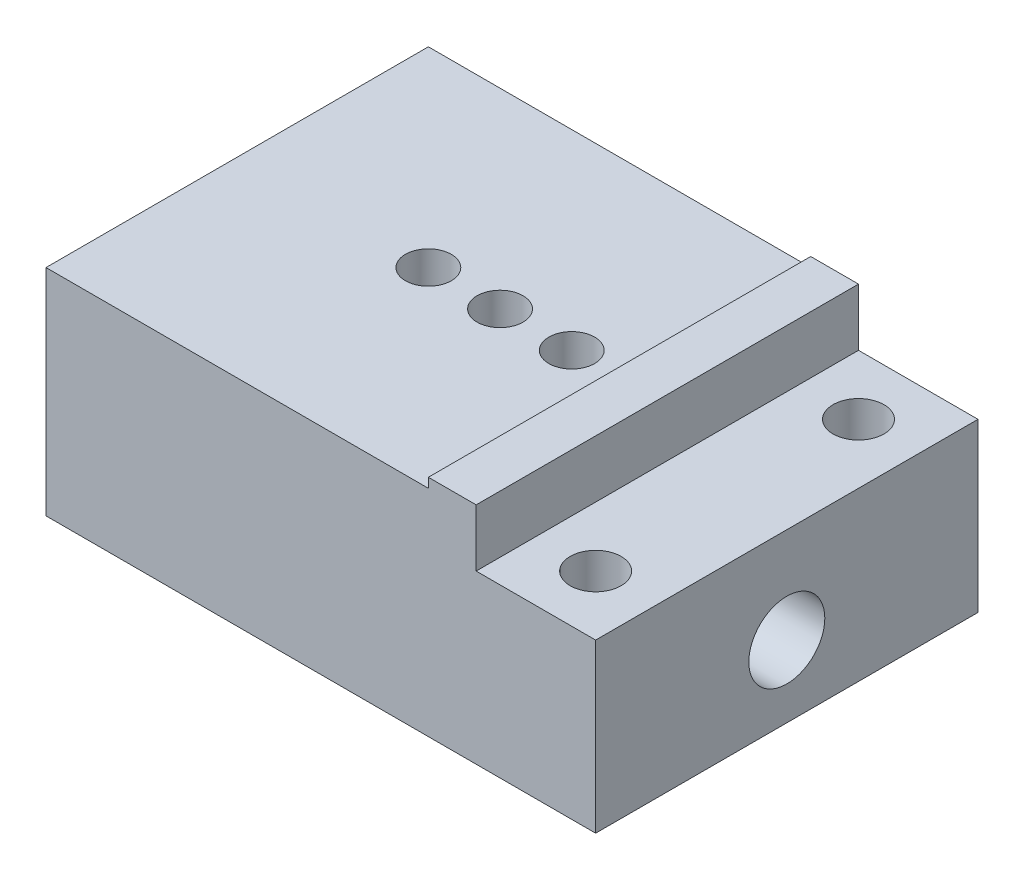
SolidWorks part; units mm, degrees
ref_plane "Front Plane" through (0, 0, 0) normal (0, 0, 1) x (1, 0, 0)
ref_plane "Top Plane" through (0, 0, 0) normal (0, 1, 0) x (1, 0, 0)
ref_plane "Right Plane" through (0, 0, 0) normal (1, 0, 0) x (0, 0, -1)
sketch "Sketch1" plane through (0, 0, 0) normal (0, 0, 1) x (1, 0, 0)
  line L1 (0, 0) -> (25.4, 0)
  line L2 (0, 0) -> (0, 11.43)
  line L3 (0, 11.43) -> (20.32, 11.43)
  line L11 (22.86, 8.89) -> (29.21, 8.89)
  line L12 (29.21, 0) -> (29.21, 8.89)
  line L14 (22.86, 8.89) -> (22.86, 11.938)
  line L15 (22.86, 11.938) -> (20.32, 11.938)
  line L16 (20.32, 11.938) -> (20.32, 11.43)
  line L17 (29.21, 0) -> (25.4, 0)
  dimension "D1" = 2.54
  dimension "D2" = 2.54
  dimension "D3" = 8.89
  dimension "D4" = 6.35
  dimension "D5" = 20.32
  dimension "D7" = 0.508
extrude "Boss-Extrude1" add sketch "Sketch1" along normal blind 20.32 contours L3 L16 L15 L14 L11 L12 L17 L1 L2
hole_wizard "#2 Clearance Hole1" positions "3DSketch1" profile "Sketch3" hole size "#2" standard "ANSI Inch"
sketch3d "3DSketch1"
  line L0 (0, 11.43, 0) -> (20.32, 11.43, 0) construction
  line L1 (20.32, 11.43, 20.32) -> (20.32, 11.43, 0) construction
  point P0 (17.78, 11.43, 10.16)
  point P2 (13.97, 11.43, 10.16)
  point P4 (10.16, 11.43, 10.16)
  dimension "D1" = 3.81
  dimension "D2" = 3.81
  dimension "D3" = 10.16
  dimension "D4" = 2.54
sketch "Sketch3" plane through (17.78, 11.43, 10.16) normal (1, 0, 0) x (0, 0, 1)
  line L0 (0, 0) -> (0, 8.3526)
  line L1 (0, 8.3526) -> (1.2192, 7.62)
  line L2 (1.2192, 7.62) -> (1.2192, 0)
  line L5 (1.2192, 0) -> (0, 0)
  line L10 (0, 8.3526) -> (-1.2192, 7.62) construction
  line L11 (0, -6.35) -> (0, 107.95) construction
  dimension "Hole Dia." = 2.4384
  dimension "Hole Depth" = 7.62
  dimension "Drill Angle" = 118
hole_wizard "Tap Drill for #10-32 Tap1" positions "3DSketch2" profile "Sketch4" hole size "#10-32" standard "ANSI Inch"
sketch3d "3DSketch2"
  line L2 (29.21, 0, 20.32) -> (29.21, 8.89, 20.32) construction
  line L3 (29.21, 8.89, 20.32) -> (29.21, 8.89, 0) construction
  point P7 (29.21, 3.81, 10.16)
  dimension "D3" = 10.16
  dimension "D4" = 5.08
sketch "Sketch4" plane through (29.21, 3.81, 10.16) normal (0, 1, 0) x (0, 0, -1)
  line L0 (0, 0) -> (0, 21.5333)
  line L1 (0, 21.5333) -> (2.0193, 20.32)
  line L2 (2.0193, 20.32) -> (2.0193, 0)
  line L5 (2.0193, 0) -> (0, 0)
  line L10 (0, 21.5333) -> (-2.0193, 20.32) construction
  line L11 (0, -6.35) -> (0, 107.95) construction
  dimension "Hole Dia." = 4.0386
  dimension "Hole Depth" = 20.32
  dimension "Drill Angle" = 118
hole_wizard "5/64 (0.07813) Diameter Hole1" positions "3DSketch3" profile "Sketch5" hole size "5/64" standard "ANSI Inch"
sketch3d "3DSketch3"
  line L0 (0, 11.43, 20.32) -> (0, 11.43, 0) construction
  line L1 (0, 0, 0) -> (0, 11.43, 0) construction
  point P0 (0, 9.652, 6.35)
  dimension "D1" = 1.778
  dimension "D2" = 6.35
sketch "Sketch5" plane through (0, 9.652, 6.35) normal (0, 1, 0) x (0, 0, 1)
  line L0 (0, 0) -> (0, 13.2962)
  line L1 (0, 13.2962) -> (0.9923, 12.7)
  line L2 (0.9923, 12.7) -> (0.9923, 0)
  line L5 (0.9923, 0) -> (0, 0)
  line L10 (0, 13.2962) -> (-0.9923, 12.7) construction
  line L11 (0, -6.35) -> (0, 107.95) construction
  dimension "Hole Dia." = 1.9845
  dimension "Hole Depth" = 12.7
  dimension "Drill Angle" = 118
hole_wizard "Tap Drill for #6-32 Tap1" positions "3DSketch4" profile "Sketch7" hole size "#6-32" standard "ANSI Inch" end condition through all
sketch3d "3DSketch4"
  line L0 (22.86, 8.89, 20.32) -> (22.86, 8.89, 0) construction
  line L1 (22.86, 8.89, 20.32) -> (29.21, 8.89, 20.32) construction
  line L2 (22.86, 8.89, 0) -> (29.21, 8.89, 0) construction
  point P0 (26.035, 8.89, 17.145)
  point P2 (26.035, 8.89, 3.175)
  dimension "D1" = 3.175
  dimension "D2" = 3.175
  dimension "D3" = 3.175
sketch "Sketch7" plane through (26.035, 8.89, 17.145) normal (1, 0, 0) x (0, 0, 1)
  line L0 (0, 0) -> (0, 8.89)
  line L1 (0, 8.89) -> (1.3525, 8.89)
  line L2 (1.3525, 8.89) -> (1.3525, 0)
  line L5 (1.3525, 0) -> (0, 0)
  line L11 (0, -6.35) -> (0, 107.95) construction
  dimension "Thru Hole Dia." = 2.7051
  dimension "Thru Hole Depth" = 8.89
